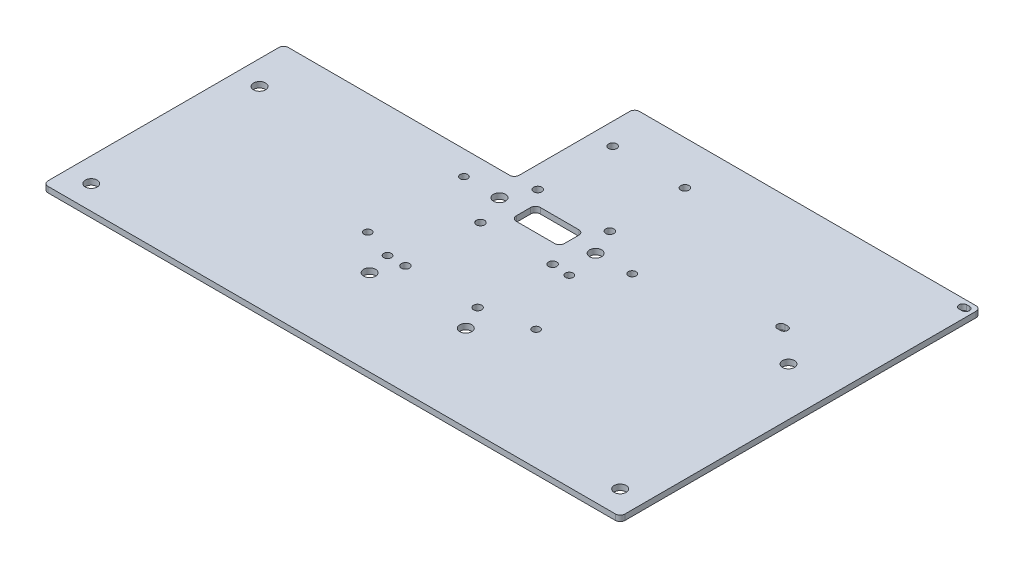
SolidWorks part; units mm, degrees
ref_plane "Front Plane" through (0, 0, 0) normal (0, 0, 1) x (1, 0, 0)
ref_plane "Top Plane" through (0, 0, 0) normal (0, 1, 0) x (1, 0, 0)
ref_plane "Right Plane" through (0, 0, 0) normal (1, 0, 0) x (0, 0, -1)
sketch "Sketch1" plane through (0, 0, 0) normal (0, 1, 0) x (1, 0, 0)
  line L1 (-126.9534, -0.978) -> (172.7666, -0.978)
  line L2 (-129.4934, -3.518) -> (-129.4934, -227.038)
  line L3 (-126.9534, -229.578) -> (172.7666, -229.578)
  line L4 (175.3066, -3.518) -> (175.3066, -227.038)
  circle A0 centre (3.8566, -23.9781) radius 2.15
  circle A1 centre (41.9566, -23.9781) radius 2.15
  circle A2 centre (3.8566, -63.6021) radius 2.15
  circle A3 centre (41.9566, -63.6021) radius 2.15
  circle A4 centre (3.8566, -93.8281) radius 2.15
  circle A5 centre (41.9566, -93.8281) radius 2.15
  circle A6 centre (3.8566, -133.4521) radius 2.15
  circle A7 centre (41.9566, -133.4521) radius 2.15
  arc A8 (172.7666, -0.978) -> (175.3066, -3.518) centre (172.7666, -3.518) cw
  arc A9 (175.3066, -227.038) -> (172.7666, -229.578) centre (172.7666, -227.038) cw
  arc A10 (-126.9534, -229.578) -> (-129.4934, -227.038) centre (-126.9534, -227.038) cw
  arc A11 (-129.4934, -3.518) -> (-126.9534, -0.978) centre (-126.9534, -3.518) cw
  point P0 (22.9066, -0.978)
  dimension "D3" = 19.05
  dimension "D4" = 2
  dimension "D5" = 2
  dimension "D7" = 2.54
  dimension "D17" = 304.8
  dimension "D2" = 2
  dimension "D11" = 23.0001
  dimension "D15" = 228.6
extrude "Boss-Extrude1" add sketch "Sketch1" along normal blind 3
sketch "Sketch2" plane through (0, 0, 0) normal (0, -1, 0) x (-1, 0, 0)
  line L0 (126.9534, -229.578) -> (-172.7666, -229.578) construction
  line L2 (-172.7666, -0.978) -> (126.9534, -0.978) construction
  circle A0 centre (21.5434, -77.178) radius 2
  circle A1 centre (-67.3566, -77.178) radius 2
  circle A2 centre (21.5434, -127.978) radius 2
  circle A3 centre (-67.3566, -127.978) radius 2
  point P4 (-22.9066, -0.978)
  point P5 (-22.9066, -229.578)
  dimension "D2" = 50.8
  dimension "D1" = 88.9
  dimension "D3" = 101.6
  dimension "D4" = 101.6
  dimension "D5" = 88.9
  dimension "D6" = 44.45
  dimension "D7" = 44.45
extrude "Cut-Extrude1" cut sketch "Sketch2" against normal through all
sketch "Sketch3" plane through (0, 0, 0) normal (0, -1, 0) x (-1, 0, 0)
  line L2 (129.4934, -3.518) -> (129.4934, -227.038) construction
  circle A0 centre (-48.3066, -77.4562) radius 3.175
  circle A1 centre (2.4934, -77.4562) radius 3.175
  circle A2 centre (2.4934, -146.0362) radius 3.175
  circle A3 centre (-48.3066, -146.0362) radius 3.175
  dimension "D1" = 2
  dimension "D4" = 50.8
  dimension "D5" = 127
  dimension "D2" = 2
extrude "Cut-Extrude2" cut sketch "Sketch3" against normal through all
sketch "Sketch4" plane through (0, 0, 0) normal (0, -1, 0) x (1, 0, 0)
  line L0 (-129.4934, 3.518) -> (-129.4934, 227.038) construction
  line L1 (-134.5734, -0.262) -> (-7.5734, -0.262)
  line L2 (-134.5734, -0.262) -> (-134.5734, 64.478)
  line L3 (-134.5734, 64.478) -> (-7.5734, 64.478)
  line L4 (-7.5734, -0.262) -> (-7.5734, 64.478)
  line L5 (172.7666, 0.978) -> (-126.9534, 0.978) construction
  dimension "D1" = 121.92
  dimension "D2" = 127
  dimension "D3" = 63.5
extrude "Cut-Extrude3" cut sketch "Sketch4" against normal through all
sketch "Sketch5" plane through (0, 0, 0) normal (0, -1, 0) x (1, 0, 0)
  line L0 (-126.9534, 229.578) -> (172.7666, 229.578) construction
  line L1 (175.3066, 258.768) -> (-129.4934, 258.768)
  line L2 (175.3066, 258.768) -> (175.3066, 191.478)
  line L3 (175.3066, 191.478) -> (-129.4934, 191.478)
  line L4 (-129.4934, 258.768) -> (-129.4934, 191.478)
  line L5 (175.3066, 227.038) -> (175.3066, 3.518) construction
  dimension "D1" = 38.1
  dimension "D2" = 304.8
  dimension "D3" = 304.8
extrude "Cut-Extrude4" cut sketch "Sketch5" against normal through all
sketch "Sketch6" plane through (0, 0, 0) normal (0, -1, 0) x (-1, 0, 0)
  line L0 (-171.3066, -4.978) -> (-169.8066, -4.978) construction
  line L1 (-171.3066, -2.978) -> (-169.8066, -2.978)
  line L2 (-171.3066, -6.978) -> (-169.8066, -6.978)
  line L3 (-172.7666, -0.978) -> (7.5734, -0.978) construction
  line L4 (-175.3066, -191.478) -> (-175.3066, -3.518) construction
  line L5 (-132.3566, -61.978) -> (-130.8066, -61.978) construction
  line L6 (-132.3566, -59.978) -> (-130.8066, -59.978)
  line L7 (-132.3566, -63.978) -> (-130.8066, -63.978)
  arc A0 (-171.3066, -2.978) -> (-171.3066, -6.978) centre (-171.3066, -4.978) ccw
  arc A1 (-169.8066, -6.978) -> (-169.8066, -2.978) centre (-169.8066, -4.978) ccw
  arc A2 (-132.3566, -59.978) -> (-132.3566, -63.978) centre (-132.3566, -61.978) ccw
  arc A3 (-130.8066, -63.978) -> (-130.8066, -59.978) centre (-130.8066, -61.978) ccw
  circle A5 centre (5.6083, -133.4521) radius 2
  circle A6 centre (-51.4066, -94.4521) radius 2
  point P3 (-170.5566, -4.978)
  point P15 (-131.5816, -61.978)
  dimension "D2" = 4
  dimension "D3" = 4
  dimension "D1" = 39
  dimension "D5" = 57
  dimension "D4" = 5.5
  dimension "D6" = 38.2
extrude "Cut-Extrude5" cut sketch "Sketch6" against normal through all
sketch "Sketch7" plane through (0, 0, 0) normal (0, -1, 0) x (1, 0, 0)
  line L0 (175.3066, 191.478) -> (175.3066, 3.518) construction
  line L2 (172.7666, 0.978) -> (-7.5734, 0.978) construction
  circle A0 centre (149.9066, 77.178) radius 3.175
  circle A1 centre (-116.7934, 89.878) radius 3.175
  circle A2 centre (-116.7934, 178.778) radius 3.175
  circle A3 centre (162.6066, 178.778) radius 3.175
  dimension "D1" = 25.4
  dimension "D2" = 76.2
extrude "Cut-Extrude6" cut sketch "Sketch7" against normal through all
sketch "Sketch8" plane through (0, 0, 0) normal (0, -1, 0) x (-1, 0, 0)
  line L1 (-12.7466, -83.8062) -> (-33.0666, -83.8062)
  line L2 (-10.2066, -81.2662) -> (-10.2066, -73.6462)
  line L3 (-12.7466, -71.1062) -> (-33.0666, -71.1062)
  line L4 (-35.6066, -81.2662) -> (-35.6066, -73.6462)
  line L5 (-10.2066, -83.8062) -> (-35.6066, -71.1062) construction
  line L6 (-10.2066, -71.1062) -> (-35.6066, -83.8062) construction
  circle A0 centre (2.4934, -77.4562) radius 3.175 construction
  arc A1 (-33.0666, -83.8062) -> (-35.6066, -81.2662) centre (-33.0666, -81.2662) cw
  arc A2 (-35.6066, -73.6462) -> (-33.0666, -71.1062) centre (-33.0666, -73.6462) cw
  arc A3 (-12.7466, -71.1062) -> (-10.2066, -73.6462) centre (-12.7466, -73.6462) cw
  arc A4 (-10.2066, -81.2662) -> (-12.7466, -83.8062) centre (-12.7466, -81.2662) cw
  point P0 (-22.9066, -77.4562)
  dimension "D4" = 2.54
  dimension "D1" = 25.4
  dimension "D2" = 12.7
  dimension "D3" = 25.4
extrude "Cut-Extrude7" cut sketch "Sketch8" against normal through all
fillet "Fillet1" radius 2.54 2 edges at (-129.4934, 1.5, 191.478) (175.3066, 1.5, 191.478)
fillet "Fillet2" radius 2.54 3 edges at (-129.4934, 1.5, 64.478) (-7.5734, 1.5, 64.478) (-7.5734, 1.5, 0.978)
